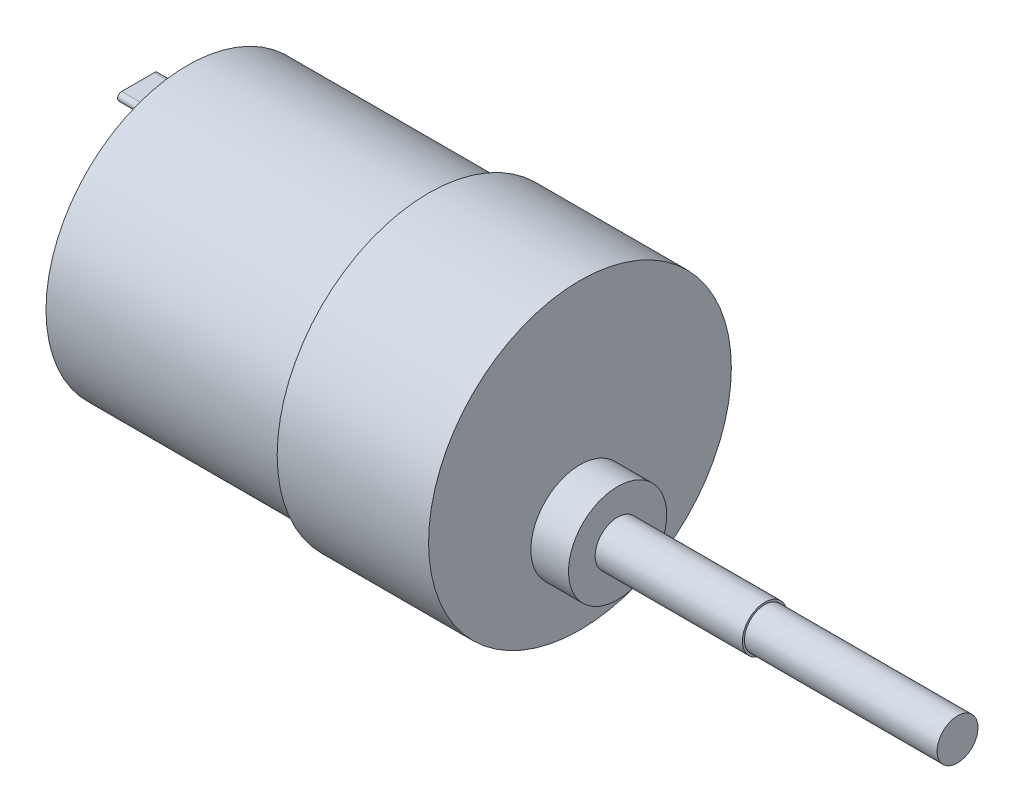
SolidWorks part; units mm, degrees
material "6061 Alloy"
ref_plane "Front Plane" through (0, 0, 0) normal (0, 0, 1) x (1, 0, 0)
ref_plane "Top Plane" through (0, 0, 0) normal (0, 1, 0) x (1, 0, 0)
ref_plane "Right Plane" through (0, 0, 0) normal (1, 0, 0) x (0, 0, -1)
sketch "Sketch1" plane through (0, 0, 0) normal (1, 0, 0) x (0, 0, -1)
  circle A0 centre (0, 0) radius 17.25
  dimension "D1" = 34.5
extrude "Boss-Extrude1" add sketch "Sketch1" along normal blind 29.5
sketch "Sketch2" plane through (29.5, 0, 0) normal (1, 0, 0) x (0, 0, -1)
  circle A0 centre (0, 0) radius 18.5
  dimension "D1" = 37
extrude "Boss-Extrude2" add sketch "Sketch2" along normal blind 18.5
sketch "Sketch3" plane through (0, 0, 0) normal (-1, 0, 0) x (0, 0, 1)
  circle A0 centre (0, 0) radius 3
  dimension "D1" = 6
extrude "Boss-Extrude3" add sketch "Sketch3" along normal blind 1.5
sketch "Sketch4" plane through (-1.5, 0, 0) normal (-1, 0, 0) x (0, 0, 1)
  circle A0 centre (0, 0) radius 1.5
  dimension "D1" = 3
extrude "Boss-Extrude4" add sketch "Sketch4" along normal blind 1.5
sketch "Sketch5" plane through (0, 0, 0) normal (-1, 0, 0) x (0, 0, 1)
  line L0 (-2, 12) -> (2, 12) construction
  line L1 (-2, 12.5) -> (2, 12.5)
  line L2 (-2, 11.5) -> (2, 11.5)
  line L3 (-1000, 0) -> (49000, 0) construction
  line L4 (-2, -12) -> (2, -12) construction
  line L5 (-2, -12.5) -> (2, -12.5)
  line L6 (-2, -11.5) -> (2, -11.5)
  circle A0 centre (0, 12) radius 2 construction
  arc A2 (-2, 12.5) -> (-2, 11.5) centre (-2, 12) ccw
  arc A3 (2, 11.5) -> (2, 12.5) centre (2, 12) ccw
  arc A4 (-2, -12.5) -> (-2, -11.5) centre (-2, -12) cw
  arc A5 (2, -11.5) -> (2, -12.5) centre (2, -12) cw
  point P4 (0, 12)
  point P14 (0, -12)
  dimension "D3" = 4
  dimension "D4" = 0.5
  dimension "D2" = 12
extrude "Boss-Extrude5" add sketch "Sketch5" along normal blind 6
sketch "Sketch7" plane through (48, 0, 0) normal (1, 0, 0) x (0, 0, -1)
  circle A0 centre (0, -7) radius 6
  point P2 (0, 0)
  dimension "D1" = 12
  dimension "D2" = 7
extrude "Boss-Extrude6" add sketch "Sketch7" along normal blind 4.6
sketch "Sketch8" plane through (52.6, 0, 0) normal (1, 0, 0) x (0, 0, -1)
  circle A0 centre (0, -7) radius 2.75
  dimension "D1" = 5.5
extrude "Boss-Extrude7" add sketch "Sketch8" along normal blind 18
sketch "Sketch9" plane through (70.6, 0, 0) normal (1, 0, 0) x (0, 0, -1)
  circle A0 centre (0, -7) radius 2.5
  dimension "D1" = 5
extrude "Boss-Extrude8" add sketch "Sketch9" along normal blind 23.54
